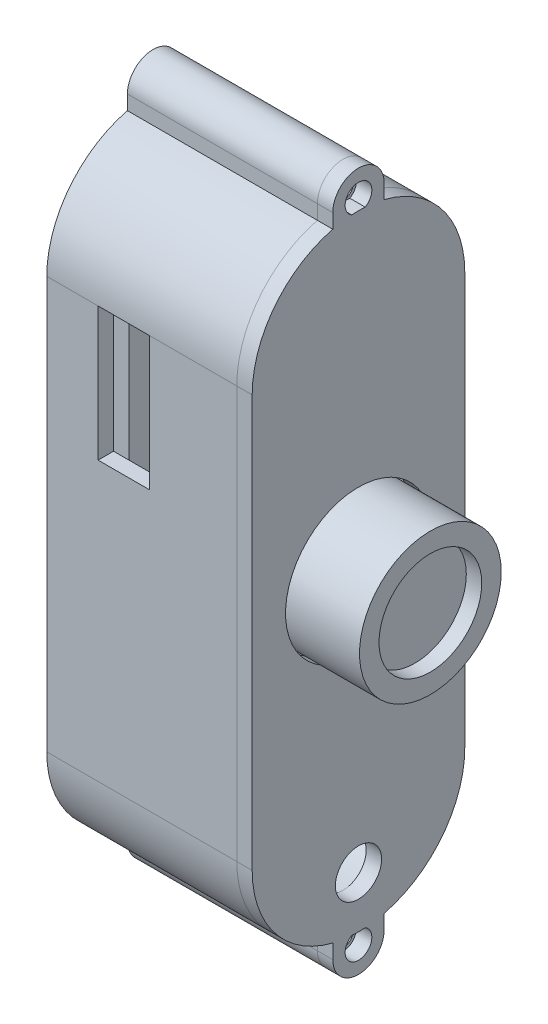
SolidWorks part; units mm, degrees
other "Camera Case Lid"
other "Mock Camera"
ref_plane "Front Plane" through (0, 0, 0) normal (1, 0, 0) x (0, 1, 0)
ref_plane "Top Plane" through (0, 0, 0) normal (0, 0, 1) x (0, 1, 0)
ref_plane "Right Plane" through (0, 0, 0) normal (0, 1, 0) x (-1, 0, 0)
sketch "Sketch1" plane through (0, 0, 0) normal (1, 0, 0) x (0, 1, 0)
  line L0 (-10.35, 10.35) -> (-10.35, 20.7) construction
  line L1 (0, 0) -> (40.1, 0)
  line L3 (0, 20.7) -> (40.1, 20.7)
  line L5 (0, 0) -> (0, 20.7) construction
  line L6 (40.1, 20.7) -> (40.1, 0) construction
  line L7 (-10.35, 20.7) -> (50.45, 20.7) construction
  line L8 (50.45, 20.7) -> (50.45, 10.35) construction
  arc A0 (40.1, 0) -> (40.1, 20.7) centre (40.1, 10.35) ccw
  arc A1 (0, 0) -> (0, 20.7) centre (0, 10.35) cw
  dimension "D1" = 20.7
  dimension "D2" = 60.8
extrude "Boss-Extrude1" add sketch "Sketch1" along normal blind 13.5
sketch "Sketch2" plane through (13.5, 0, 0) normal (1, 0, 0) x (0, 1, 0)
  line L4 (40.1, 19.2) -> (0, 19.2)
  line L5 (0, 1.5) -> (40.1, 1.5)
  line L6 (40.1, 19.2) -> (0, 19.2)
  line L7 (0, 1.5) -> (40.1, 1.5)
  arc A4 (40.1, 1.5) -> (40.1, 19.2) centre (40.1, 10.35) ccw
  arc A5 (0, 19.2) -> (0, 1.5) centre (0, 10.35) ccw
  arc A6 (40.1, 1.5) -> (40.1, 19.2) centre (40.1, 10.35) ccw
  arc A7 (0, 19.2) -> (0, 1.5) centre (0, 10.35) ccw
  dimension "D1" = 1.5
extrude "Cut-Extrude1" cut sketch "Sketch2" against normal blind 12
sketch "Sketch3" plane through (1.5, 0, 0) normal (1, 0, 0) x (0, 1, 0)
  line L0 (0.92, 10.35) -> (43.92, 10.35) construction
  line L1 (20.05, 19.2) -> (20.05, 1.5) construction
  line L2 (40.1, 19.2) -> (0, 19.2) construction
  line L3 (0, 1.5) -> (40.1, 1.5) construction
  line L5 (16.55, 19.2) -> (23.55, 19.2)
  line L6 (16.55, 19.2) -> (16.55, 15.7)
  line L7 (16.55, 15.7) -> (23.55, 15.7)
  line L8 (23.55, 19.2) -> (23.55, 15.7)
  circle A0 centre (43.92, 10.35) radius 1
  circle A1 centre (0.92, 10.35) radius 1
  circle A2 centre (0.92, 10.35) radius 1.6
  circle A3 centre (43.92, 10.35) radius 2.5
  arc A4 (0, 19.2) -> (0, 1.5) centre (0, 10.35) ccw construction
  point P12 (20.05, 10.35)
  point P18 (-8.85, 10.35)
  point P24 (20.05, 19.2)
  dimension "D1" = 2
  dimension "D2" = 5
  dimension "D3" = 43
  dimension "D7" = 3.2
  dimension "D4" = 9.77
  dimension "D5" = 7
  dimension "D6" = 3.5
extrude "Boss-Extrude2" add sketch "Sketch3" along normal blind 3
sketch "Sketch5" plane through (13.5, 0, 0) normal (1, 0, 0) x (0, 1, 0)
  line L0 (-10.35, 10.35) -> (50.45, 10.35) construction
  line L2 (40.1, 20.7) -> (0, 20.7)
  line L3 (0, 0) -> (40.1, 0)
  line L4 (40.1, 20.7) -> (0, 20.7)
  line L5 (0, 0) -> (40.1, 0)
  circle A0 centre (20.05, 10.35) radius 7.1
  arc A2 (40.1, 0) -> (40.1, 20.7) centre (40.1, 10.35) ccw
  arc A3 (0, 20.7) -> (0, 0) centre (0, 10.35) ccw
  arc A4 (40.1, 0) -> (40.1, 20.7) centre (40.1, 10.35) ccw
  arc A5 (0, 20.7) -> (0, 0) centre (0, 10.35) ccw
  dimension "D2" = 14.2
  dimension "D1" = 0
extrude "Boss-Extrude3" add sketch "Sketch5" along normal blind 1.5 separate body
sketch "Sketch6" plane through (13.5, 0, 0) normal (-1, 0, 0) x (0, -1, 0)
  line L1 (-40.1, 19.2) -> (0, 19.2)
  line L4 (-40.1, 19) -> (0, 19) construction
  line L5 (0, 1.7) -> (-40.1, 1.7) construction
  line L6 (-40.1, 18) -> (0, 18)
  line L7 (0, 2.7) -> (-40.1, 2.7)
  line L8 (0, 1.5) -> (-40.1, 1.5)
  arc A0 (0, 1.5) -> (0, 19.2) centre (0, 10.35) ccw
  arc A4 (0, 1.7) -> (0, 19) centre (0, 10.35) ccw construction
  arc A5 (-40.1, 19) -> (-40.1, 1.7) centre (-40.1, 10.35) ccw construction
  arc A6 (0, 2.7) -> (0, 18) centre (0, 10.35) ccw
  arc A7 (-40.1, 18) -> (-40.1, 2.7) centre (-40.1, 10.35) ccw
  arc A8 (-40.1, 19.2) -> (-40.1, 1.5) centre (-40.1, 10.35) ccw
  dimension "D1" = 0.2
  dimension "D2" = 1
extrude "Boss-Extrude4" add sketch "Sketch6" along normal blind 3.5 contours A5 L5 A4 L4 | L6 A6 L7 A7 | L1 A0 L8 A8
sketch "Sketch8" plane through (15, 0, 0) normal (1, 0, 0) x (0, 1, 0)
  line L0 (-10.35, 10.35) -> (50.45, 10.35) construction
  circle A0 centre (-5.35, 10.35) radius 2.25
  arc A1 (0, 20.7) -> (0, 0) centre (0, 10.35) ccw construction
  arc A2 (40.1, 0) -> (40.1, 20.7) centre (40.1, 10.35) ccw construction
  point P5 (-10.35, 10.35)
  dimension "D2" = 4.5
  dimension "D1" = 5
extrude "Cut-Extrude3" cut sketch "Sketch8" against normal up to next (1.5 mm away) contours A0
sketch "Sketch9" plane through (0, 0, 20.7) normal (0, 0, 1) x (1, 0, 0)
  line L1 (0, 40.1) -> (5, 40.1)
  line L2 (0, 40.1) -> (0, 27.1)
  line L3 (0, 27.1) -> (5, 27.1)
  line L4 (5, 40.1) -> (5, 27.1)
  dimension "D1" = 5
  dimension "D2" = 13
extrude "Cut-Extrude4" cut sketch "Sketch9" against normal up to surface (1.5 mm away) contours L4 L3 L2 L1 up to face at (5.25, 20.05, 19.2)
sketch "Sketch10" plane through (0, 0, 0) normal (-1, 0, 0) x (0, -1, 0)
  line L0 (-20.05, 0) -> (-20.05, 20.7) construction
  line L5 (11.45, 7.85) -> (10.0435, 7.85)
  line L6 (11.45, 12.85) -> (10.0435, 12.85)
  line L7 (0, 0) -> (-40.1, 0) construction
  line L8 (-27.1, 20.7) -> (0, 20.7) construction
  line L9 (-51.55, 10.35) -> (-20.05, 10.35) construction
  line L10 (-51.55, 12.85) -> (-50.1435, 12.85)
  line L11 (-51.55, 7.85) -> (-50.1435, 7.85)
  arc A4 (-50.1435, 12.85) -> (-50.2299, 12.4731) centre (-40.1, 10.35) ccw
  arc A5 (-51.55, 12.85) -> (-51.55, 7.85) centre (-51.55, 10.35) ccw
  circle A6 centre (-51.55, 10.35) radius 1
  arc A7 (-40.1, 20.7) -> (-40.1, 0) centre (-40.1, 10.35) ccw construction
  arc A8 (-50.2299, 8.2269) -> (-50.2299, 12.4731) centre (-51.55, 10.35) ccw
  arc A9 (-50.2299, 8.2269) -> (-50.1435, 7.85) centre (-40.1, 10.35) ccw
  arc A10 (10.1299, 8.2269) -> (10.0435, 7.85) centre (0, 10.35) cw
  arc A11 (10.1299, 8.2269) -> (10.1299, 12.4731) centre (11.45, 10.35) cw
  circle A12 centre (11.45, 10.35) radius 1
  arc A13 (11.45, 12.85) -> (11.45, 7.85) centre (11.45, 10.35) cw
  arc A14 (10.0435, 12.85) -> (10.1299, 12.4731) centre (0, 10.35) cw
  dimension "D3" = 31.5
  dimension "D1" = 2
  dimension "D2" = 5
extrude "Boss-Extrude5" add sketch "Sketch10" against normal up to vertex
sketch "Sketch11" plane through (15, 0, 0) normal (1, 0, 0) x (0, 1, 0)
  line L6 (50.1435, 7.85) -> (51.55, 7.85)
  line L7 (51.55, 12.85) -> (50.1435, 12.85)
  line L8 (40.1, 20.7) -> (0, 20.7)
  line L9 (-10.0435, 12.85) -> (-11.45, 12.85)
  line L10 (-11.45, 7.85) -> (-10.0435, 7.85)
  line L11 (0, 0) -> (40.1, 0)
  line L12 (50.1435, 7.85) -> (51.55, 7.85)
  line L13 (51.55, 12.85) -> (50.1435, 12.85)
  line L14 (40.1, 20.7) -> (0, 20.7)
  line L15 (-10.0435, 12.85) -> (-11.45, 12.85)
  line L16 (-11.45, 7.85) -> (-10.0435, 7.85)
  line L17 (0, 0) -> (40.1, 0)
  circle A0 centre (-5.35, 10.35) radius 2.25 construction
  circle A1 centre (-5.35, 10.35) radius 2.25
  circle A2 centre (51.55, 10.35) radius 1 construction
  circle A3 centre (-11.45, 10.35) radius 1 construction
  circle A4 centre (51.55, 10.35) radius 1 construction
  circle A5 centre (-11.45, 10.35) radius 1 construction
  arc A6 (40.1, 0) -> (50.1435, 7.85) centre (40.1, 10.35) ccw
  arc A7 (51.55, 7.85) -> (51.55, 12.85) centre (51.55, 10.35) ccw
  arc A8 (50.1435, 12.85) -> (40.1, 20.7) centre (40.1, 10.35) ccw
  arc A9 (0, 20.7) -> (-10.0435, 12.85) centre (0, 10.35) ccw
  arc A10 (-11.45, 12.85) -> (-11.45, 7.85) centre (-11.45, 10.35) ccw
  arc A11 (-10.0435, 7.85) -> (0, 0) centre (0, 10.35) ccw
  arc A12 (40.1, 0) -> (50.1435, 7.85) centre (40.1, 10.35) ccw
  arc A13 (51.55, 7.85) -> (51.55, 12.85) centre (51.55, 10.35) ccw
  arc A14 (50.1435, 12.85) -> (40.1, 20.7) centre (40.1, 10.35) ccw
  arc A15 (0, 20.7) -> (-10.0435, 12.85) centre (0, 10.35) ccw
  arc A16 (-11.45, 12.85) -> (-11.45, 7.85) centre (-11.45, 10.35) ccw
  arc A17 (-10.0435, 7.85) -> (0, 0) centre (0, 10.35) ccw
  circle A18 centre (20.05, 10.35) radius 7.1 construction
  circle A19 centre (20.05, 10.35) radius 7.1
  circle A20 centre (-11.45, 10.35) radius 1.3
  circle A21 centre (51.55, 10.35) radius 1.3
  dimension "D1" = 0
  dimension "D2" = 0.3
extrude "Boss-Extrude6" add sketch "Sketch11" against normal up to surface (1.5 mm away) up to face at (13.5, 20.05, 10.35)
sketch "Sketch12" plane through (1.5, 0, 0) normal (1, 0, 0) x (0, 0, -1)
  circle A0 centre (-10.35, 20.05) radius 6.9
  dimension "D1" = 13.8
extrude "Boss-Extrude7" add sketch "Sketch12" along normal blind 20.5 separate body contours A0
sketch "Sketch13" plane through (22, 0, 0) normal (1, 0, 0) x (0, 1, 0)
  circle A0 centre (20.05, 10.35) radius 5
  dimension "D1" = 10
extrude "Cut-Extrude5" cut sketch "Sketch13" against normal blind 1.5 contours A0
sketch "Sketch16" plane through (0, 0, 0) normal (-1, 0, 0) x (0, -1, 0)
  line L0 (-40.1, 20.7) -> (-27.1, 20.7)
  line L9 (-50.1435, 12.85) -> (-51.55, 12.85)
  line L10 (-51.55, 7.85) -> (-50.1435, 7.85)
  line L11 (-40.1, 0) -> (0, 0)
  line L12 (10.0435, 7.85) -> (11.45, 7.85)
  line L13 (11.45, 12.85) -> (10.0435, 12.85)
  line L14 (0, 20.7) -> (-27.1, 20.7)
  line L15 (-27.1, 20.7) -> (-27.1, 19.2)
  line L16 (-27.1, 19.2) -> (-40.1, 19.2)
  line L17 (-40.1, 19.2) -> (-40.1, 20.7)
  line L18 (-50.1435, 12.85) -> (-51.55, 12.85)
  line L19 (-51.55, 7.85) -> (-50.1435, 7.85)
  line L20 (-40.1, 0) -> (0, 0)
  line L21 (10.0435, 7.85) -> (11.45, 7.85)
  line L22 (11.45, 12.85) -> (10.0435, 12.85)
  line L23 (0, 20.7) -> (-27.1, 20.7)
  arc A6 (-40.1, 20.7) -> (-50.1435, 12.85) centre (-40.1, 10.35) ccw
  arc A7 (-51.55, 12.85) -> (-51.55, 7.85) centre (-51.55, 10.35) ccw
  arc A8 (-50.1435, 7.85) -> (-40.1, 0) centre (-40.1, 10.35) ccw
  arc A9 (0, 0) -> (10.0435, 7.85) centre (0, 10.35) ccw
  arc A10 (11.45, 7.85) -> (11.45, 12.85) centre (11.45, 10.35) ccw
  arc A11 (10.0435, 12.85) -> (0, 20.7) centre (0, 10.35) ccw
  arc A12 (-40.1, 20.7) -> (-50.1435, 12.85) centre (-40.1, 10.35) ccw
  arc A13 (-51.55, 12.85) -> (-51.55, 7.85) centre (-51.55, 10.35) ccw
  arc A14 (-50.1435, 7.85) -> (-40.1, 0) centre (-40.1, 10.35) ccw
  arc A15 (0, 0) -> (10.0435, 7.85) centre (0, 10.35) ccw
  arc A16 (11.45, 7.85) -> (11.45, 12.85) centre (11.45, 10.35) ccw
  arc A17 (10.0435, 12.85) -> (0, 20.7) centre (0, 10.35) ccw
  dimension "D1" = 0
extrude "Boss-Extrude8" add sketch "Sketch16" along normal blind 5
sketch "Sketch17" plane through (-5, 0, 0) normal (-1, 0, 0) x (0, -1, 0)
  line L0 (-35.05, 10.35) -> (-5.05, 10.35) construction
  line L1 (-20.05, 20.7) -> (-20.05, 0) construction
  line L2 (0, 20.7) -> (-40.1, 20.7) construction
  line L3 (-40.1, 0) -> (0, 0) construction
  line L4 (-35.05, 10.35) -> (-54.05, 10.35) construction
  line L5 (13.95, 10.35) -> (-5.05, 10.35) construction
  circle A0 centre (-35.05, 10.35) radius 1.475
  circle A1 centre (-5.05, 10.35) radius 1.475
  arc A2 (-51.55, 12.85) -> (-51.55, 7.85) centre (-51.55, 10.35) ccw construction
  arc A3 (11.45, 7.85) -> (11.45, 12.85) centre (11.45, 10.35) ccw construction
  point P10 (-20.05, 10.35)
  point P11 (-20.05, 10.35)
  dimension "D1" = 2.95
  dimension "D2" = 30
extrude "Cut-Extrude6" cut sketch "Sketch17" against normal blind 5
